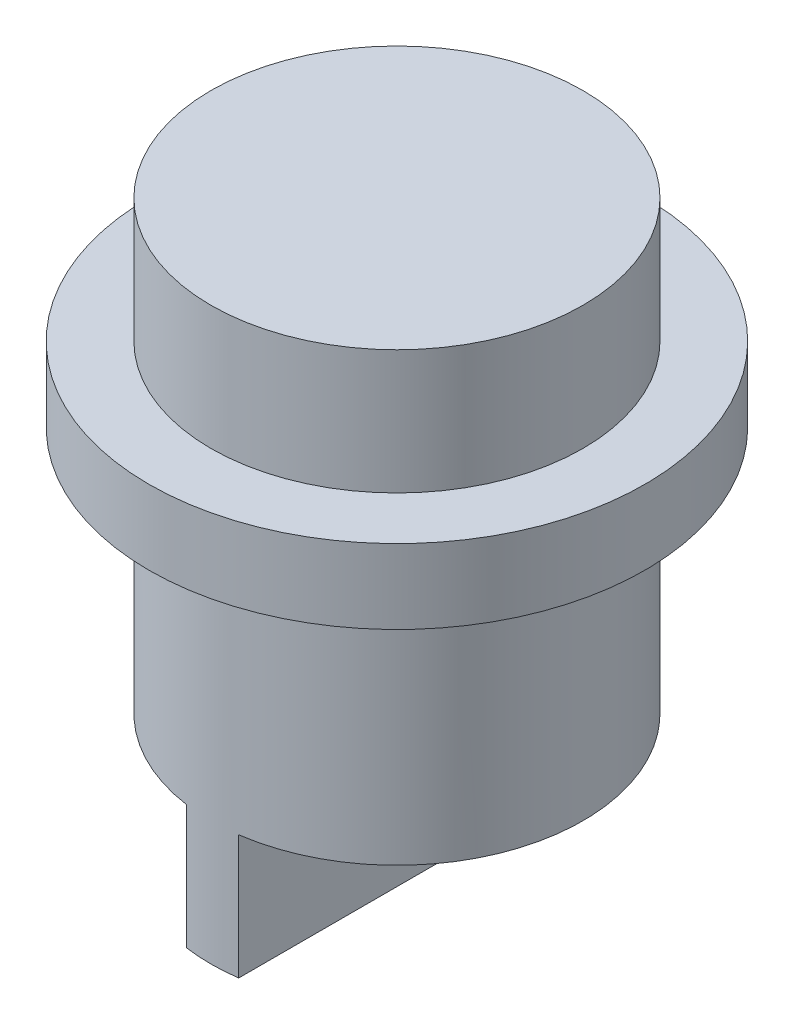
SolidWorks part; units mm, degrees
ref_plane "前视基准面" through (0, 0, 0) normal (0, 0, 1) x (1, 0, 0)
ref_plane "上视基准面" through (0, 0, 0) normal (0, 1, 0) x (1, 0, 0)
ref_plane "右视基准面" through (0, 0, 0) normal (1, 0, 0) x (0, 0, -1)
sketch "草图1" plane through (0, 0, 0) normal (0, 1, 0) x (1, 0, 0)
  circle A0 centre (0, 0) radius 7.5
  dimension "D1" = 15
extrude "凸台-拉伸1" add sketch "草图1" along normal blind 10
sketch "草图2" plane through (0, 10, 0) normal (0, 1, 0) x (1, 0, 0)
  circle A0 centre (0, 0) radius 10
  dimension "D1" = 20
extrude "凸台-拉伸2" add sketch "草图2" along normal blind 3
sketch "草图3" plane through (0, 13, 0) normal (0, 1, 0) x (1, 0, 0)
  circle A0 centre (0, 0) radius 7.5 construction
  circle A1 centre (0, 0) radius 7.5
extrude "凸台-拉伸3" add sketch "草图3" along normal blind 5
sketch "草图4" plane through (0, 0, 0) normal (0, -1, 0) x (1, 0, 0)
  line L2 (-1.0481, 7.4264) -> (-1.0481, -7.4264)
  line L4 (1.0481, 7.4264) -> (1.0481, -7.4264)
  line L5 (0, -7.4264) -> (0, 7.4264) construction
  line L6 (-1.0481, 0) -> (1.0481, 0) construction
  circle A0 centre (0, 0) radius 7.5 construction
  arc A1 (1.0481, 7.4264) -> (-1.0481, 7.4264) centre (0, 0) ccw
  circle A2 centre (0, 0) radius 7.5
  arc A3 (-1.0481, -7.4264) -> (1.0481, -7.4264) centre (0, 0) ccw
  point P0 (0, 0)
  dimension "D1" = 0
extrude "凸台-拉伸4" add sketch "草图4" along normal blind 5
